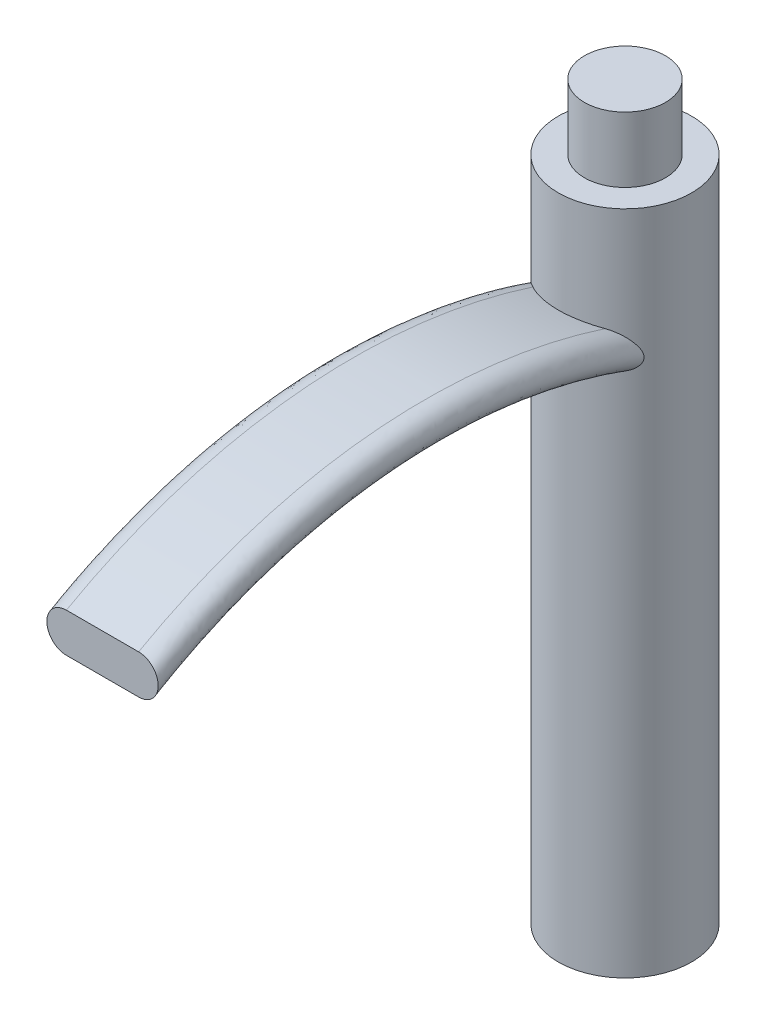
SolidWorks part; units mm, degrees
ref_plane "Front Plane" through (0, 0, 0) normal (0, 0, 1) x (1, 0, 0)
ref_plane "Top Plane" through (0, 0, 0) normal (0, 1, 0) x (1, 0, 0)
ref_plane "Right Plane" through (0, 0, 0) normal (1, 0, 0) x (0, 0, -1)
sketch "Sketch1" plane through (0, 0, 0) normal (0, 1, 0) x (1, 0, 0)
  circle A0 centre (0, 0) radius 25.5
  dimension "D1" = 51
extrude "Boss-Extrude1" add sketch "Sketch1" along normal blind 255 contours A0
sketch "Sketch2" plane through (0, 0, 0) normal (0, 0, 1) x (1, 0, 0)
  line L0 (0, 0) -> (0, 104.54)
  line L1 (0, 104.54) -> (0, 199.54)
  line L2 (-13.8197, 199.54) -> (13.8197, 199.54) construction
  line L3 (-13.8197, 207.0367) -> (13.8197, 207.0367)
  line L4 (-13.8197, 192.0433) -> (13.8197, 192.0433)
  arc A0 (-13.8197, 207.0367) -> (-13.8197, 192.0433) centre (-13.8197, 199.54) ccw
  arc A1 (13.8197, 192.0433) -> (13.8197, 207.0367) centre (13.8197, 199.54) ccw
  point P6 (0, 199.54)
  dimension "D1" = 104.54
  dimension "D2" = 95
ref_plane "Plane1" through (0, 0, 200) normal (0, 0, 1) x (1, 0, 0)
sketch "Sketch3" plane through (0, 0, 200) normal (0, 0, 1) x (1, 0, 0)
  line L0 (-13.8197, 189.54) -> (13.8197, 189.54) construction
  line L6 (-13.8197, 197.0301) -> (13.8197, 197.0301)
  line L7 (-13.8197, 182.0499) -> (13.8197, 182.0499)
  arc A4 (-13.8197, 197.0301) -> (-13.8197, 182.0499) centre (-13.8197, 189.54) ccw
  arc A5 (13.8197, 182.0499) -> (13.8197, 197.0301) centre (13.8197, 189.54) ccw
  point P9 (0, 189.54)
  dimension "D1" = 10
sketch "Sketch4" plane through (0, 0, 0) normal (1, 0, 0) x (0, 0, -1)
  arc A0 (-200, 189.54) -> (0, 199.54) centre (-90.4242, 3.0236) cw
sweep "Sweep1" add profiles "Sketch3" path "Sketch4"
sketch "Sketch5" plane through (0, 255, 0) normal (0, 1, 0) x (1, 0, 0)
  circle A0 centre (0, 0) radius 15.5
  dimension "D1" = 31
extrude "Boss-Extrude2" add sketch "Sketch5" along normal blind 25
